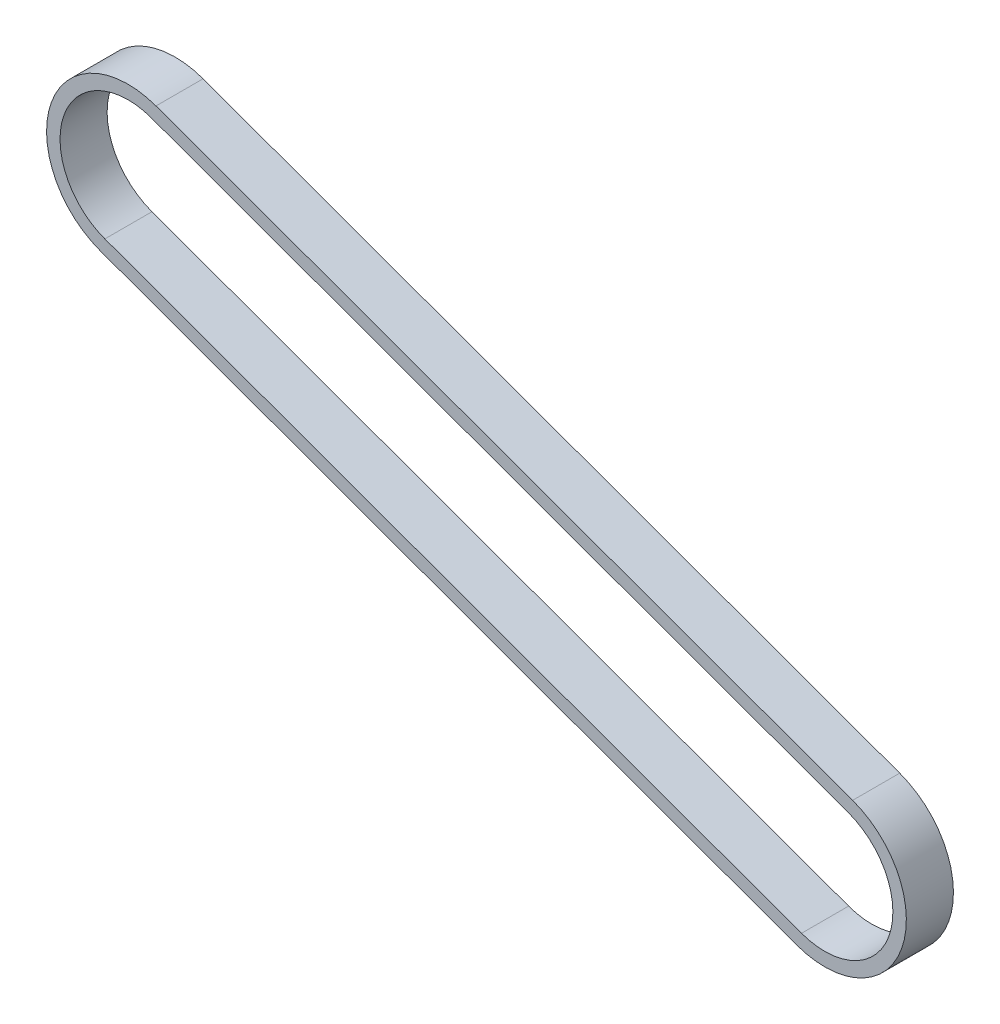
SolidWorks part; units mm, degrees
material "BUTYL"
ref_plane "前视基准面" through (0, 0, 0) normal (0, 0, 1) x (1, 0, 0)
ref_plane "上视基准面" through (0, 0, 0) normal (0, 1, 0) x (1, 0, 0)
ref_plane "右视基准面" through (0, 0, 0) normal (1, 0, 0) x (0, 0, -1)
sketch "草图2" plane through (0, 0, 0) normal (0, 0, 1) x (1, 0, 0)
  line L0 (0, 0) -> (1, 0) construction
  line L1 (0, 0) -> (0, 1) construction
  line L2 (-6.7996, 9.5168) -> (96.7735, -28.0976)
  line L3 (89.8611, -47.1313) -> (-13.712, -9.5168)
  arc A0 (-13.712, -9.5168) -> (-6.7996, 9.5168) centre (-10.2558, 0) cw
  arc A1 (96.7735, -28.0976) -> (89.8611, -47.1313) centre (93.3173, -37.6144) cw
extrude "拉伸-薄壁1" add sketch "草图2" along normal mid plane 7 thin thin type one direction wall 2
